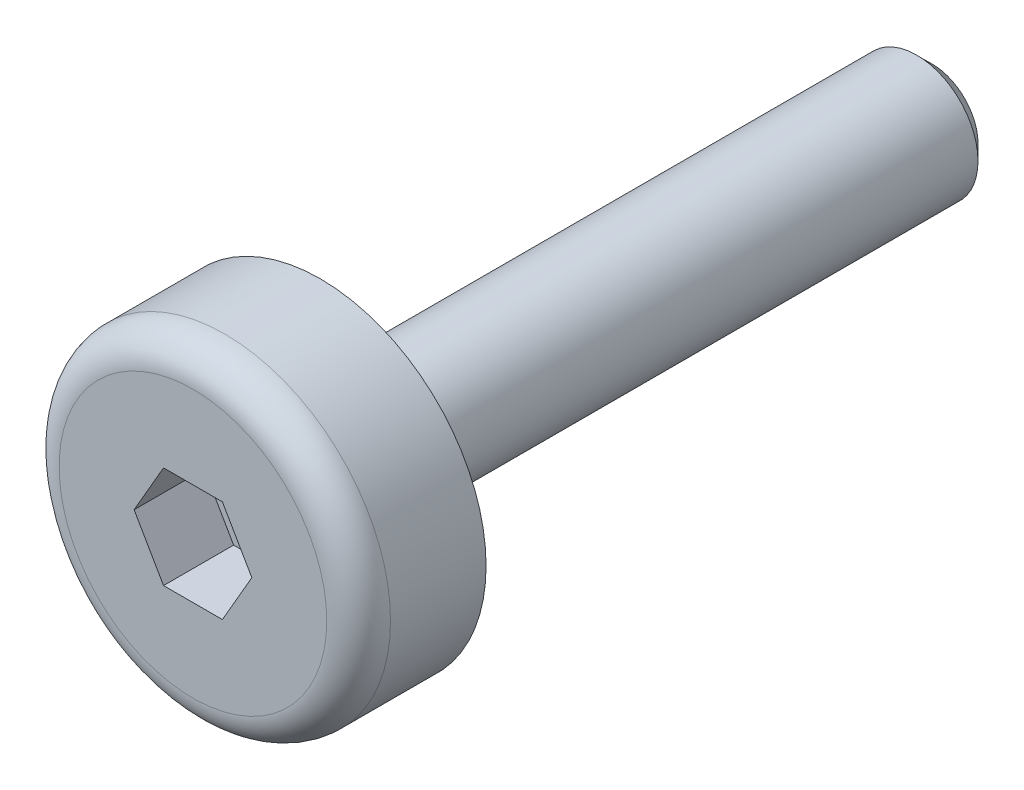
SolidWorks part; units mm, degrees
ref_plane "Front Plane" through (0, 0, 0) normal (0, 0, 1) x (1, 0, 0)
ref_plane "Top Plane" through (0, 0, 0) normal (0, 1, 0) x (1, 0, 0)
ref_plane "Right Plane" through (0, 0, 0) normal (1, 0, 0) x (0, 0, -1)
sketch "Screw Section" plane through (0, 0, 0) normal (0, 1, 0) x (1, 0, 0)
  line L0 (0, 12) -> (1.2, 12)
  line L1 (1.2, 12) -> (1.2, 0)
  line L2 (1.2, 0) -> (3.25, 0)
  line L3 (3.25, 0) -> (3.25, -2.5)
  line L4 (3.25, -2.5) -> (0, -2.5)
  line L5 (0, -2.5) -> (0, 12)
  line L6 (0, -10.123) -> (0, 10.123) construction
  dimension "D1" = 1.2
  dimension "D2" = 3.25
  dimension "D3" = 12
  dimension "D4" = 2.5
  dimension "D5" = 10.123
  dimension "D6" = 10.123
revolve "Screw Blank Revolve" add sketch "Screw Section" angle 360 about L6
chamfer "Shank Tip Chamfer" distance 0.3 1 edges at (1.2, 0, -12)
fillet "Pan Head Round" radius 0.625 1 edges at (3.25, 0, 2.5)
ref_plane "Head Crown Plane" through (0, 0, 2.5) normal (0, 0, 1) x (1, 0, 0)
sketch "Hex Drive Sketch" plane through (0, 0, 2.5) normal (0, 0, 1) x (1, 0, 0)
  line L1 (1.1547, 0) -> (0.5774, 1)
  line L2 (0.5774, 1) -> (-0.5774, 1)
  line L3 (-0.5774, 1) -> (-1.1547, 0)
  line L4 (-1.1547, 0) -> (-0.5774, -1)
  line L5 (-0.5774, -1) -> (0.5774, -1)
  line L6 (0.5774, -1) -> (1.1547, 0)
  circle A0 centre (0, 0) radius 1 construction
  dimension "D1" = 2
extrude "Hex Drive Cut" cut sketch "Hex Drive Sketch" against normal blind 1.375
equation "\"nominal_length\"= 12.0mm 'Screw length: under pan head or including flat head"
equation "\"model_shank_radius\"= 1.2mm 'Clearance envelope minor shank radius; thread is not modeled"
equation "\"head_diameter\"= 6.5mm 'Head outside diameter"
equation "\"head_height\"= 2.5mm 'Head axial height"
equation "\"drive_across_flats\"= 2mm 'Hex drive across flats"
equation "\"tip_chamfer\"= 0.3mm 'Shank tip chamfer"
equation "\"head_round\"= 0.625mm 'Pan head crown edge radius"
equation "\"drive_depth\"= 1.375mm 'Hex socket depth"
equation "\"axis_reference_halfspan\"= 10.123mm 'Half display length of the construction axis; avoids sharing a profile endpoint"
equation "\"D1@Screw Section\"= \"model_shank_radius\""
equation "\"D2@Screw Section\"= \"head_diameter\" / 2"
equation "\"D3@Screw Section\"= \"nominal_length\""
equation "\"D4@Screw Section\"= \"head_height\""
equation "\"D5@Screw Section\"= \"axis_reference_halfspan\""
equation "\"D6@Screw Section\"= \"axis_reference_halfspan\""
equation "\"full_turn\"= 360deg 'Full circular extent for revolves and patterns"
equation "\"D1@Screw Blank Revolve\"= \"full_turn\""
equation "\"D1@Shank Tip Chamfer\"= \"tip_chamfer\""
equation "\"D1@Pan Head Round\"= \"head_round\""
equation "\"D1@Head Crown Plane\"= \"head_height\""
equation "\"D1@Hex Drive Sketch\"= \"drive_across_flats\""
equation "\"D1@Hex Drive Cut\"= \"drive_depth\""
